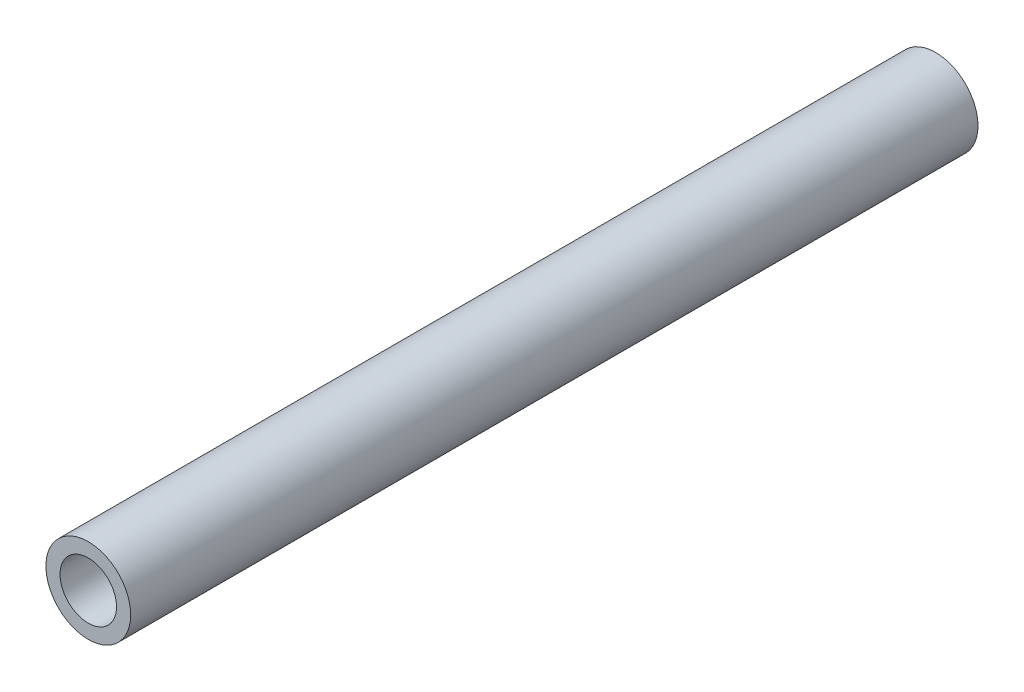
SolidWorks part; units mm, degrees
material "Thornel VCB-20 Carbon Cloth"
ref_plane "Front Plane" through (0, 0, 0) normal (0, 0, 1) x (1, 0, 0)
ref_plane "Top Plane" through (0, 0, 0) normal (0, 1, 0) x (1, 0, 0)
ref_plane "Right Plane" through (0, 0, 0) normal (1, 0, 0) x (0, 0, -1)
sketch "Sketch1" plane through (0, 0, 0) normal (0, 0, 1) x (1, 0, 0)
  circle A0 centre (-0.9922, 0.0115) radius 1.5
  circle A1 centre (-0.9922, 0.0115) radius 1
  point P4 (0, 0)
  dimension "D1" = 3
  dimension "D2" = 2
extrude "Boss-Extrude1" add sketch "Sketch1" along normal blind 30
